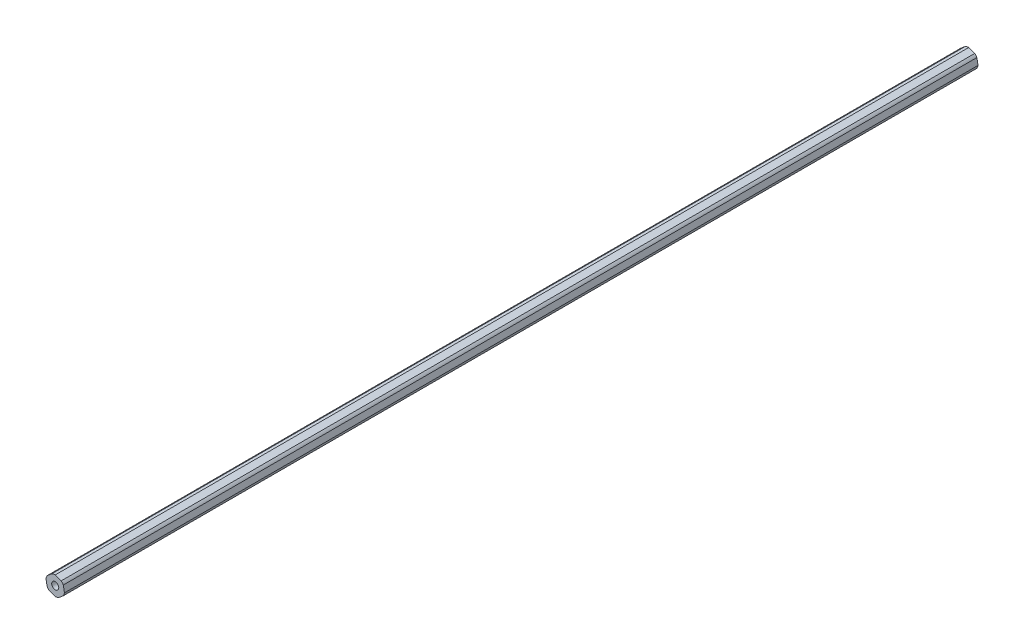
SolidWorks part; units mm, degrees
material "7075-T6 (SN)"
ref_plane "Front Plane" through (0, 0, 0) normal (0, 0, 1) x (1, 0, 0)
ref_plane "Top Plane" through (0, 0, 0) normal (0, 1, 0) x (1, 0, 0)
ref_plane "Right Plane" through (0, 0, 0) normal (1, 0, 0) x (0, 0, -1)
sketch "Sketch1" plane through (0, 0, 0) normal (0, 0, 1) x (1, 0, 0)
  line L1 (-6.6545, 1.1312) -> (-5.8457, -3.375)
  line L2 (-4.3069, -5.1974) -> (0, -6.75)
  line L3 (2.3476, -6.3286) -> (5.8457, -3.375)
  line L4 (6.6545, -1.1312) -> (5.8457, 3.375)
  line L5 (4.3069, 5.1974) -> (0, 6.75)
  line L6 (-2.3476, 6.3286) -> (-5.8457, 3.375)
  circle A0 centre (0, 0) radius 6.35 construction
  arc A1 (-5.8457, 3.375) -> (-6.6545, 1.1312) centre (0, 0) ccw
  arc A2 (-5.8457, -3.375) -> (-4.3069, -5.1974) centre (0, 0) ccw
  arc A3 (0, -6.75) -> (2.3476, -6.3286) centre (0, 0) ccw
  arc A4 (5.8457, -3.375) -> (6.6545, -1.1312) centre (0, 0) ccw
  arc A5 (5.8457, 3.375) -> (4.3069, 5.1974) centre (0, 0) ccw
  arc A6 (0, 6.75) -> (-2.3476, 6.3286) centre (0, 0) ccw
  dimension "D1" = 12.7
  dimension "D2" = 13.5
extrude "Boss-Extrude1" add sketch "Sketch1" along normal blind 658.9014
sketch "Sketch2" plane through (0, 0, 658.9014) normal (0, 0, 1) x (1, 0, 0)
  circle A0 centre (0, 0) radius 2.0193
  dimension "D1" = 4.0386
extrude "Cut-Extrude1" cut sketch "Sketch2" against normal through all
hole_wizard "1/4-20 Tapped Hole1" positions "Sketch5" profile "Sketch6" tap size "1/4-20" standard "ANSI Inch"
sketch "Sketch5" plane through (0, 0, 658.9014) normal (0, 0, 1) x (1, 0, 0)
  point P0 (0, 0)
sketch "Sketch6" plane through (0, 0, 658.9014) normal (1, 0, 0) x (0, -1, 0)
  line L0 (0, 0) -> (0, 20.5838)
  line L1 (0, 20.5838) -> (2.5527, 19.05)
  line L2 (2.5527, 19.05) -> (2.5527, 0)
  line L5 (2.5527, 0) -> (0, 0)
  line L10 (0, 20.5838) -> (-2.5527, 19.05) construction
  line L11 (0, -6.35) -> (0, 107.95) construction
  dimension "Tap Drill Dia." = 5.1054
  dimension "Tap Drill Depth" = 19.05
  dimension "Drill Angle" = 118
cosmetic thread "Hole Thread1" parameters "D1"=12.7, "D2"=6.35
hole_wizard "1/4-20 Tapped Hole2" positions "Sketch7" profile "Sketch8" tap size "1/4-20" standard "ANSI Inch"
sketch "Sketch7" plane through (0, 0, 0) normal (0, 0, -1) x (-1, 0, 0)
  point P0 (0, 0)
sketch "Sketch8" plane through (0, 0, 0) normal (1, 0, 0) x (0, 1, 0)
  line L0 (0, 0) -> (0, 20.5838)
  line L1 (0, 20.5838) -> (2.5527, 19.05)
  line L2 (2.5527, 19.05) -> (2.5527, 0)
  line L5 (2.5527, 0) -> (0, 0)
  line L10 (0, 20.5838) -> (-2.5527, 19.05) construction
  line L11 (0, -6.35) -> (0, 107.95) construction
  dimension "Tap Drill Dia." = 5.1054
  dimension "Tap Drill Depth" = 19.05
  dimension "Drill Angle" = 118
cosmetic thread "Hole Thread2" parameters "D1"=12.7, "D2"=6.35
